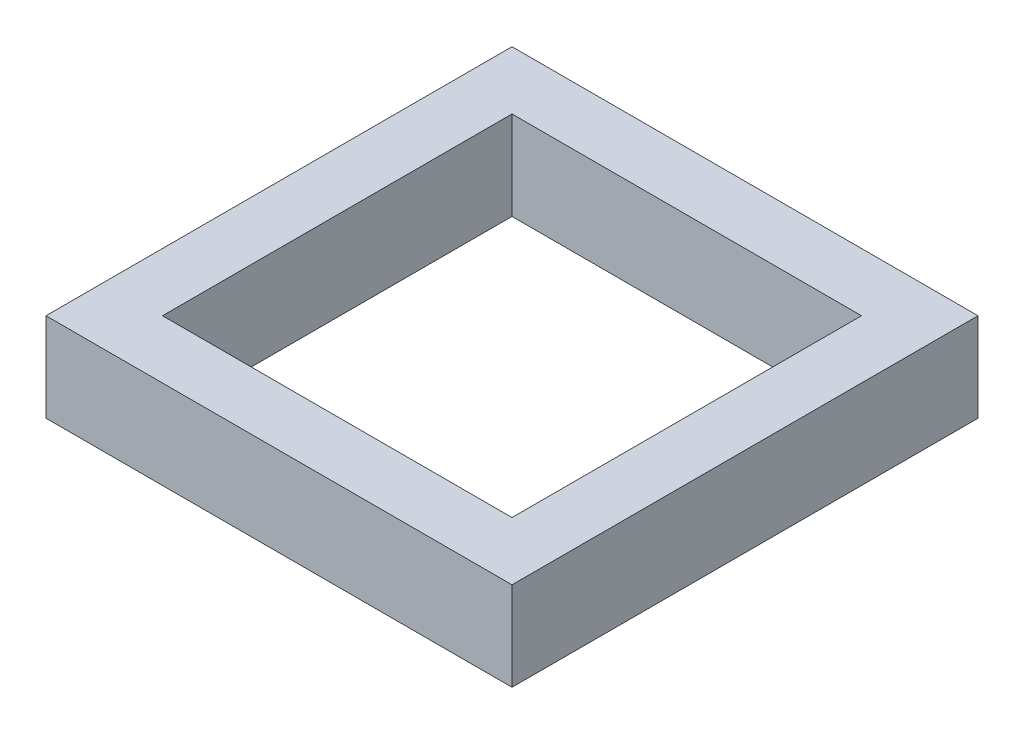
SolidWorks part; units mm, degrees
ref_plane "Front Plane" through (0, 0, 0) normal (0, 0, 1) x (1, 0, 0)
ref_plane "Top Plane" through (0, 0, 0) normal (0, 1, 0) x (1, 0, 0)
ref_plane "Right Plane" through (0, 0, 0) normal (1, 0, 0) x (0, 0, -1)
sketch "Sketch1" plane through (0, 0, 0) normal (0, 1, 0) x (1, 0, 0)
  line L0 (-10.3409, 11.0889) -> (16.3251, 11.0889)
  line L1 (-7.0079, 7.7559) -> (12.9921, 7.7559)
  line L2 (-7.0079, 7.7559) -> (-7.0079, -12.2441)
  line L3 (-7.0079, -12.2441) -> (12.9921, -12.2441)
  line L4 (12.9921, 7.7559) -> (12.9921, -12.2441)
  line L5 (16.3251, 11.0889) -> (16.3251, -15.5771)
  line L6 (-10.3409, -15.5771) -> (16.3251, -15.5771)
  line L7 (-10.3409, 11.0889) -> (-10.3409, -15.5771)
  dimension "D1" = 20
  dimension "D2" = 20
  dimension "D3" = 3.333
extrude "Boss-Extrude1" add sketch "Sketch1" along normal blind 5.08
